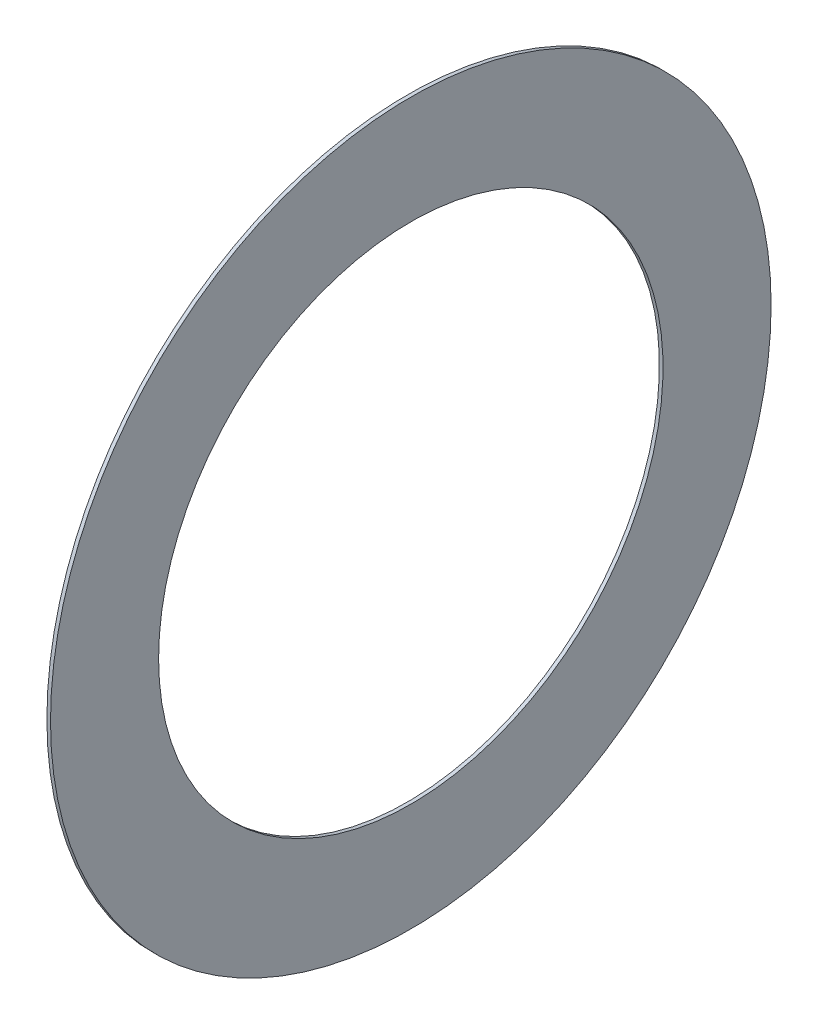
SolidWorks part; units mm, degrees
material "Plain Carbon Steel"
ref_plane "Front Plane" through (0, 0, 0) normal (0, 0, 1) x (1, 0, 0)
ref_plane "Top Plane" through (0, 0, 0) normal (0, 1, 0) x (1, 0, 0)
ref_plane "Right Plane" through (0, 0, 0) normal (1, 0, 0) x (0, 0, -1)
sketch "Sketch1" plane through (0, 0, 0) normal (0, 0, 1) x (1, 0, 0)
  line L0 (-13.3412, 0) -> (20.9725, 0) construction
  line L1 (0.05, 7) -> (-0.05, 7)
  line L2 (0.05, 7) -> (0.05, 10)
  line L3 (0.05, 10) -> (-0.05, 10)
  line L4 (-0.05, 7) -> (-0.05, 10)
  line L5 (0.05, 7) -> (-0.05, 10) construction
  line L6 (0.05, 10) -> (-0.05, 7) construction
  point P0 (0, 8.5)
  point P6 (0, 0)
  dimension "D1" = 14
  dimension "D2" = 20
  dimension "D3" = 0.1
revolve "Revolve1" add sketch "Sketch1" angle 360 about L0
